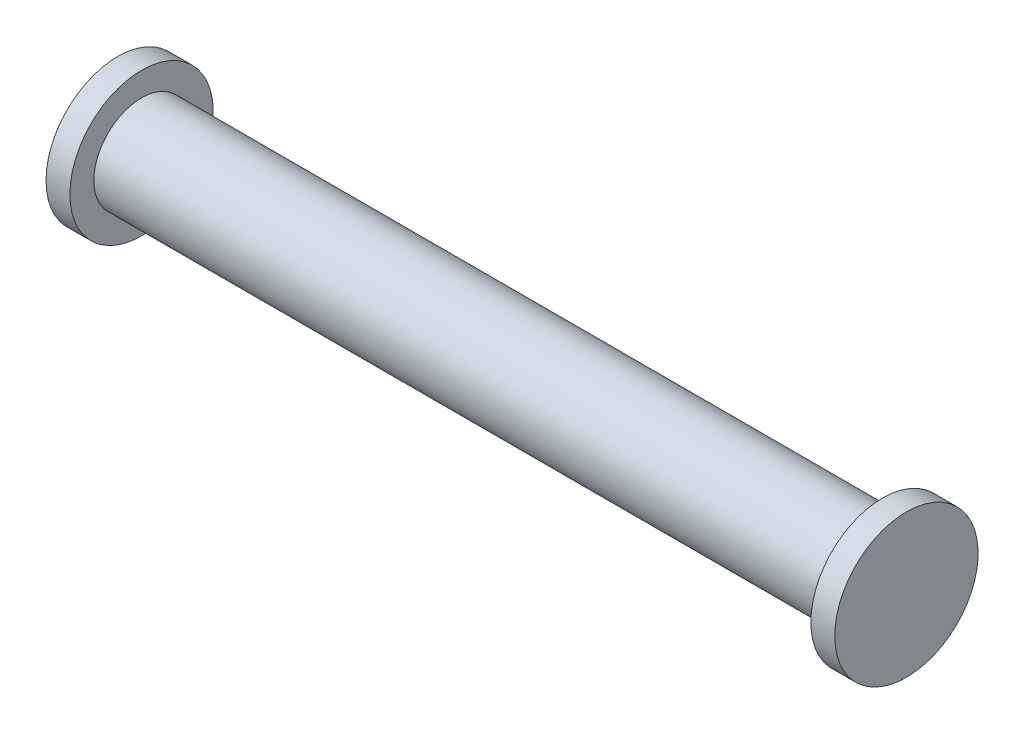
SolidWorks part; units mm, degrees
material "AISI 304"
ref_plane "Alzado" through (0, 0, 0) normal (0, 0, 1) x (1, 0, 0)
ref_plane "Planta" through (0, 0, 0) normal (0, 1, 0) x (1, 0, 0)
ref_plane "Vista lateral" through (0, 0, 0) normal (1, 0, 0) x (0, 0, -1)
sketch "Sketch1" plane through (0, 0, 0) normal (0, 0, 1) x (1, 0, 0)
  line L0 (-14, 0) -> (-14, 4.5)
  line L1 (-14, 4.5) -> (-12.5, 4.5)
  line L2 (-12.5, 4.5) -> (-12.5, 3)
  line L3 (-12.5, 3) -> (34, 3)
  line L4 (34, 3) -> (34, 4.5)
  line L5 (34, 4.5) -> (35.5, 4.5)
  line L6 (35.5, 4.5) -> (35.5, 0)
  line L7 (35.5, 0) -> (-14, 0)
  line L8 (-18, 0) -> (39.5, 0) construction
revolve "Pasador_codo" add sketch "Sketch1" angle 360 about L8
